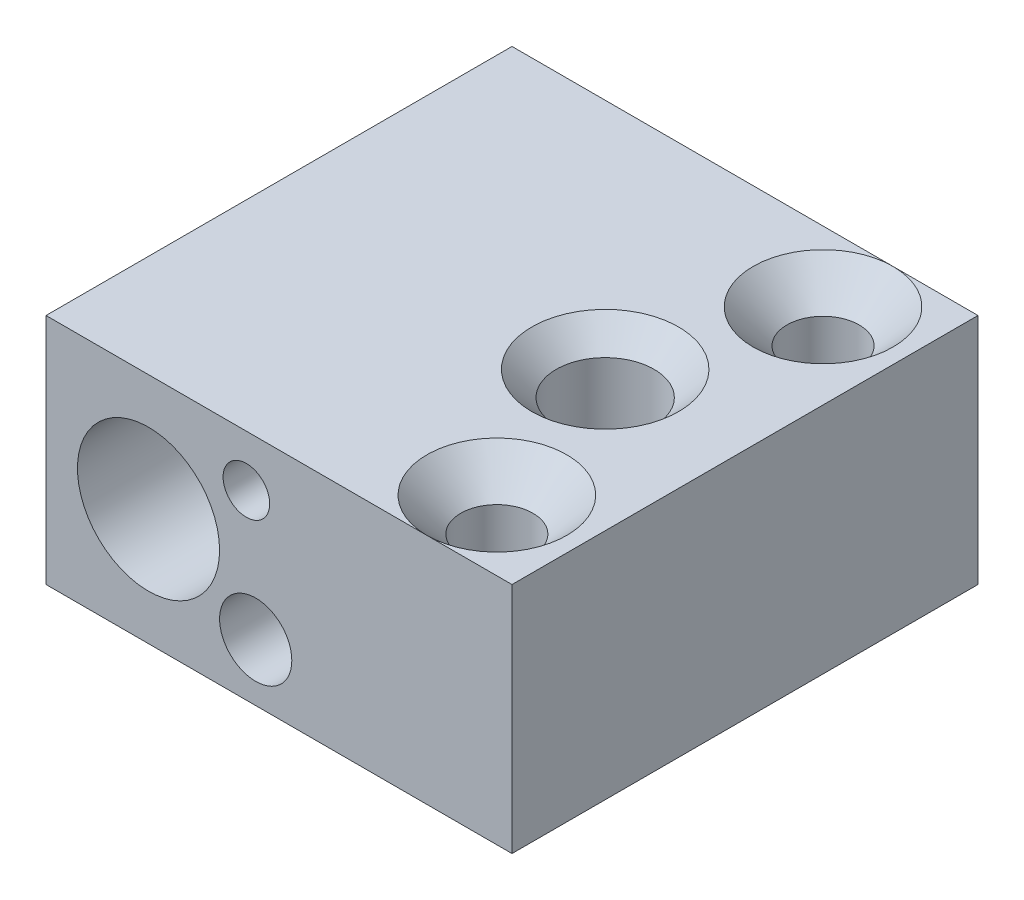
SolidWorks part; units mm, degrees
ref_plane "前视基准面" through (0, 0, 0) normal (0, 0, 1) x (1, 0, 0)
ref_plane "上视基准面" through (0, 0, 0) normal (0, 1, 0) x (1, 0, 0)
ref_plane "右视基准面" through (0, 0, 0) normal (1, 0, 0) x (0, 0, -1)
sketch "草图1" plane through (0, 0, 0) normal (0, 1, 0) x (1, 0, 0)
  line L1 (-10, -10) -> (10, -10)
  line L2 (-10, -10) -> (-10, 10)
  line L3 (-10, 10) -> (10, 10)
  line L4 (10, -10) -> (10, 10)
  line L5 (-10, -10) -> (10, 10) construction
  line L6 (-10, 10) -> (10, -10) construction
  point P0 (0, 0)
  dimension "D1" = 20
  dimension "D2" = 20
extrude "凸台-拉伸1" add sketch "草图1" along normal blind 10
hole_wizard "M3x0.5 螺纹孔的螺纹孔钻头1" positions "草图2" profile "草图3" hole size "M3x0.5" standard "ANSI Metric" end condition up to next
sketch "草图2" plane through (0, 10, 0) normal (0, 1, 0) x (1, 0, 0)
  line L0 (10, 10) -> (-10, 10) construction
  line L1 (10, -10) -> (10, 10) construction
  line L2 (-10, -10) -> (10, -10) construction
  point P0 (6.35, 7)
  point P2 (6.35, -7)
  dimension "D1" = 3
  dimension "D2" = 3.65
  dimension "D3" = 3
  dimension "D4" = 3.65
sketch "草图3" plane through (6.35, 10, -7) normal (1, 0, 0) x (0, 0, 1)
  line L0 (0, 0) -> (0, 10)
  line L1 (0, 10) -> (2.05, 10)
  line L2 (1.55, 9.5) -> (1.55, 1.45)
  line L3 (1.55, 1.45) -> (3, 0)
  line L5 (3, 0) -> (0, 0)
  line L6 (-1.55, 1.45) -> (-3, 0) construction
  line L7 (2.05, 10) -> (1.55, 9.5)
  line L8 (-2.05, 10) -> (-1.55, 9.5) construction
  line L11 (0, -6.35) -> (0, 107.95) construction
  dimension "通孔孔直径" = 3.1
  dimension "通孔孔深度" = 10
  dimension "近端锥形沉头孔直径" = 6
  dimension "近端锥形沉头孔角度" = 90
  dimension "远端锥形沉头孔直径" = 4.1
  dimension "远端锥形沉头孔角度" = 90
hole_wizard "M5x0.8 螺纹孔的螺纹孔钻头1" positions "草图4" profile "草图5" hole size "M5x0.8" standard "ANSI Metric" end condition up to next
sketch "草图4" plane through (0, 10, 0) normal (0, 1, 0) x (1, 0, 0)
  line L0 (10, -10) -> (10, 10) construction
  point P0 (4, 0)
  dimension "D1" = 6
sketch "草图5" plane through (4, 10, 0) normal (1, 0, 0) x (0, 0, 1)
  line L0 (0, 0) -> (0, 10)
  line L1 (0, 10) -> (3.15, 10)
  line L2 (2.1, 8.95) -> (2.1, 1.05)
  line L3 (2.1, 1.05) -> (3.15, 0)
  line L5 (3.15, 0) -> (0, 0)
  line L6 (-2.1, 1.05) -> (-3.15, 0) construction
  line L7 (3.15, 10) -> (2.1, 8.95)
  line L8 (-3.15, 10) -> (-2.1, 8.95) construction
  line L11 (0, -6.35) -> (0, 107.95) construction
  dimension "通孔孔直径" = 4.2
  dimension "通孔孔深度" = 10
  dimension "近端锥形沉头孔直径" = 6.3
  dimension "近端锥形沉头孔角度" = 90
  dimension "远端锥形沉头孔直径" = 6.3
  dimension "远端锥形沉头孔角度" = 90
sketch "草图6" plane through (0, 0, 10) normal (0, 0, 1) x (1, 0, 0)
  line L0 (-10, 10) -> (-10, 0) construction
  line L1 (-10, 0) -> (10, 0) construction
  line L2 (-10, 10) -> (6.35, 10) construction
  circle A0 centre (-5.6, 5) radius 3.05
  circle A1 centre (-1.4, 7.8) radius 1
  circle A2 centre (-1, 2.45) radius 1.55
  dimension "D1" = 6.1
  dimension "D2" = 2
  dimension "D3" = 3.1
  dimension "D4" = 4.4
  dimension "D5" = 5
  dimension "D6" = 8.6
  dimension "D7" = 2.2
  dimension "D8" = 2.45
  dimension "D9" = 9
extrude "切除-拉伸1" cut sketch "草图6" against normal up to next
hole_wizard "M3 螺旋的螺纹孔钻头0" positions "草图7" profile "草图8" hole size "M3x0.5" standard "ANSI Metric"
sketch "草图7" plane through (0, 0, -10) normal (0, 0, -1) x (-1, 0, 0)
  line L0 (10, 10) -> (10, 0) construction
  line L1 (-6.35, 10) -> (10, 10) construction
  point P0 (-2.5, 5.15)
  dimension "D1" = 12.5
  dimension "D2" = 4.85
sketch "草图8" plane through (2.5, 5.15, -10) normal (1, 0, 0) x (0, 1, 0)
  line L0 (0, 0) -> (0, 7.4464)
  line L1 (0, 7.4464) -> (1.575, 6.5)
  line L2 (1.575, 6.5) -> (1.575, 0.025)
  line L3 (1.575, 0.025) -> (1.6, 0)
  line L5 (1.6, 0) -> (0, 0)
  line L6 (-1.575, 0.025) -> (-1.6, 0) construction
  line L10 (0, 7.4464) -> (-1.575, 6.5) construction
  line L11 (0, -6.35) -> (0, 107.95) construction
  dimension "孔直径" = 3.15
  dimension "孔深度" = 6.5
  dimension "近端锥形沉头孔直径" = 3.2
  dimension "近端锥形沉头孔角度" = 90
  dimension "导头角度" = 118
sketch "草图9" plane through (-10, 0, 0) normal (1, 0, 0) x (0, 0, -1)
  line L0 (10, 6) -> (-10, 6) construction
  line L1 (10, 10) -> (10, 0) construction
  line L2 (-10, 10) -> (-10, 0) construction
  line L3 (-10, 0) -> (10, 0) construction
  text T0 "Oldgerman" font "ISOCPEUR" height 2
  dimension "D1" = 6
extrude "切除-拉伸2" cut sketch "草图9" along normal blind 0.01
